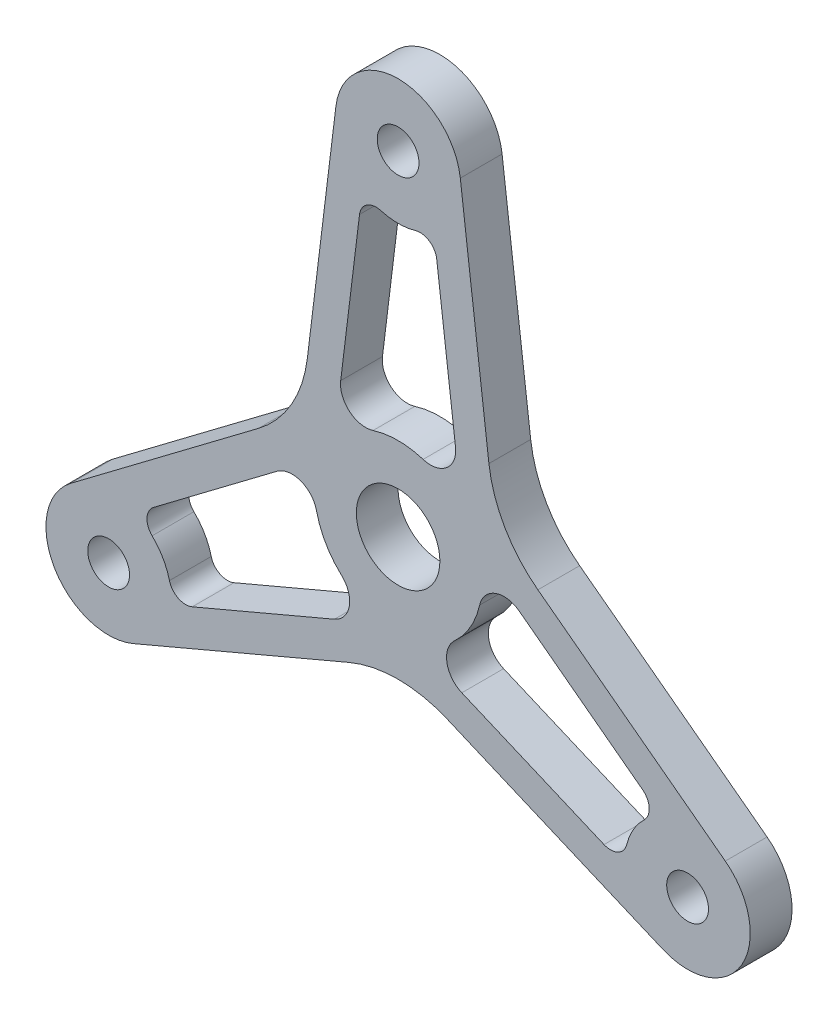
SolidWorks part; units mm, degrees
ref_plane "Front Plane" through (0, 0, 0) normal (0, 0, 1) x (1, 0, 0)
ref_plane "Top Plane" through (0, 0, 0) normal (0, 1, 0) x (1, 0, 0)
ref_plane "Right Plane" through (0, 0, 0) normal (1, 0, 0) x (0, 0, -1)
sketch "Sketch1" plane through (0, 0, 0) normal (0, 0, 1) x (1, 0, 0)
  line L0 (0, 0) -> (0, 80) construction
  line L1 (-14.8882, 81.828) -> (-21.7328, 26.0828)
  line L2 (-9.2343, 62.2313) -> (-13.7396, 25.5386)
  line L3 (-6.9478, 80.8531) -> (-15.6791, 9.7429) construction
  line L4 (14.8882, 81.828) -> (21.7328, 26.0828)
  line L5 (9.2343, 62.2313) -> (13.7396, 25.5386)
  line L6 (78.3093, -28.0205) -> (33.4548, 5.7798)
  line L7 (58.511, -23.1185) -> (28.9868, -0.8704)
  line L8 (63.4211, -53.8076) -> (11.7219, -31.8626)
  line L9 (49.2767, -39.1128) -> (15.2472, -24.6681)
  line L10 (0, 0) -> (69.282, -40) construction
  line L11 (-63.4211, -53.8076) -> (-11.7219, -31.8626)
  line L12 (-49.2767, -39.1128) -> (-15.2472, -24.6681)
  line L13 (-78.3093, -28.0205) -> (-33.4548, 5.7798)
  line L14 (-58.511, -23.1185) -> (-28.9868, -0.8704)
  line L15 (0, 0) -> (-69.282, -40) construction
  line L16 (-14.8882, 81.828) -> (-23.6194, 10.7179) construction
  circle A0 centre (0, 0) radius 10
  arc A1 (5.9879, 19.0826) -> (-5.9879, 19.0826) centre (0, 0) ccw
  circle A2 centre (0, 80) radius 5
  arc A3 (14.8882, 81.828) -> (-14.8882, 81.828) centre (0, 80) ccw
  arc A4 (-4.1559, 65.5872) -> (-9.2343, 62.2313) centre (-5.2641, 61.7438) ccw
  arc A5 (-13.7396, 25.5386) -> (-5.9879, 19.0826) centre (-7.7843, 24.8073) ccw
  arc A6 (13.7396, 25.5386) -> (5.9879, 19.0826) centre (7.7843, 24.8073) cw
  arc A7 (4.1559, 65.5872) -> (9.2343, 62.2313) centre (5.2641, 61.7438) cw
  arc A8 (-4.1559, 65.5872) -> (4.1559, 65.5872) centre (0, 80) ccw
  circle A9 centre (0, 0) radius 10
  arc A10 (13.532, -14.727) -> (19.52, -4.3556) centre (0, 0) ccw
  circle A11 centre (69.282, -40) radius 5
  arc A12 (63.4211, -53.8076) -> (78.3093, -28.0205) centre (69.282, -40) ccw
  arc A13 (58.8781, -29.1945) -> (58.511, -23.1185) centre (56.1037, -26.313) ccw
  arc A14 (28.9868, -0.8704) -> (19.52, -4.3556) centre (25.3759, -5.6623) ccw
  arc A15 (15.2472, -24.6681) -> (13.532, -14.727) centre (17.5916, -19.1451) cw
  arc A16 (54.7222, -36.3927) -> (49.2767, -39.1128) centre (50.8396, -35.4307) cw
  arc A17 (58.8781, -29.1945) -> (54.7222, -36.3927) centre (69.282, -40) ccw
  circle A18 centre (0, 0) radius 10
  arc A19 (-19.52, -4.3556) -> (-13.532, -14.727) centre (0, 0) ccw
  circle A20 centre (-69.282, -40) radius 5
  arc A21 (-78.3093, -28.0205) -> (-63.4211, -53.8076) centre (-69.282, -40) ccw
  arc A22 (-54.7222, -36.3927) -> (-49.2767, -39.1128) centre (-50.8396, -35.4307) ccw
  arc A23 (-15.2472, -24.6681) -> (-13.532, -14.727) centre (-17.5916, -19.1451) ccw
  arc A24 (-28.9868, -0.8704) -> (-19.52, -4.3556) centre (-25.3759, -5.6623) cw
  arc A25 (-58.8781, -29.1945) -> (-58.511, -23.1185) centre (-56.1037, -26.313) cw
  arc A26 (-54.7222, -36.3927) -> (-58.8781, -29.1945) centre (-69.282, -40) ccw
  arc A27 (-11.7219, -31.8626) -> (11.7219, -31.8626) centre (0, -59.4777) cw
  arc A28 (21.7328, 26.0828) -> (33.4548, 5.7798) centre (51.5092, 29.7389) ccw
  arc A29 (-33.4548, 5.7798) -> (-21.7328, 26.0828) centre (-51.5092, 29.7389) ccw
  point P64 (0, 0)
  dimension "D1" = 20
  dimension "D2" = 7
  dimension "D4" = 80
  dimension "D5" = 4
  dimension "D6" = 6
  dimension "D7" = 10
  dimension "D8" = 15
  dimension "D9" = 20
  dimension "D11" = 30
  dimension "D3" = 8
  dimension "D10" = 3
extrude "Boss-Extrude1" add sketch "Sketch1" along normal blind 10 contours A29 L13 A21 L11 A27 L8 A12 L6 A28 L4 A3 L1 A20 A11 A2 A0 A4 A8 A7 L5 A6 A1 A5 L2 A13 A17 A16 L9 A15 A10 A14 L7 A22 A26 A25 L14 A24 A19 A23 L12
